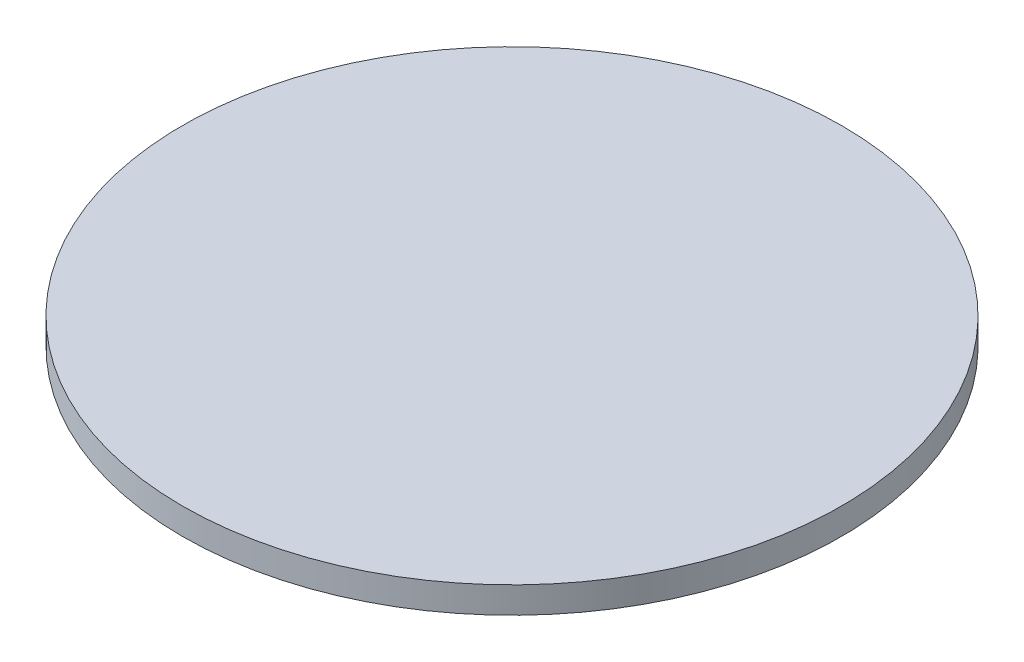
SolidWorks part; units mm, degrees
material "ABS"
ref_plane "Front Plane" through (0, 0, 0) normal (0, 0, 1) x (1, 0, 0)
ref_plane "Top Plane" through (0, 0, 0) normal (0, 1, 0) x (1, 0, 0)
ref_plane "Right Plane" through (0, 0, 0) normal (1, 0, 0) x (0, 0, -1)
sketch "Sketch1" plane through (0, 0, 0) normal (0, 1, 0) x (1, 0, 0)
  circle A0 centre (0, 0) radius 12.5
  dimension "D1" = 25
extrude "Boss-Extrude1" add sketch "Sketch1" along normal blind 1
sketch "Sketch2" plane through (0, 1, 0) normal (0, 1, 0) x (1, 0, 0)
  circle A0 centre (0, 11) radius 1
  circle A1 centre (9.5263, 5.5) radius 1
  circle A2 centre (9.5263, -5.5) radius 1
  circle A3 centre (0, -11) radius 1
  circle A4 centre (-9.5263, -5.5) radius 1
  circle A5 centre (-9.5263, 5.5) radius 1
  point P15 (0, 0)
  dimension "D1" = 2
  dimension "D2" = 11
  dimension "D3" = 6
